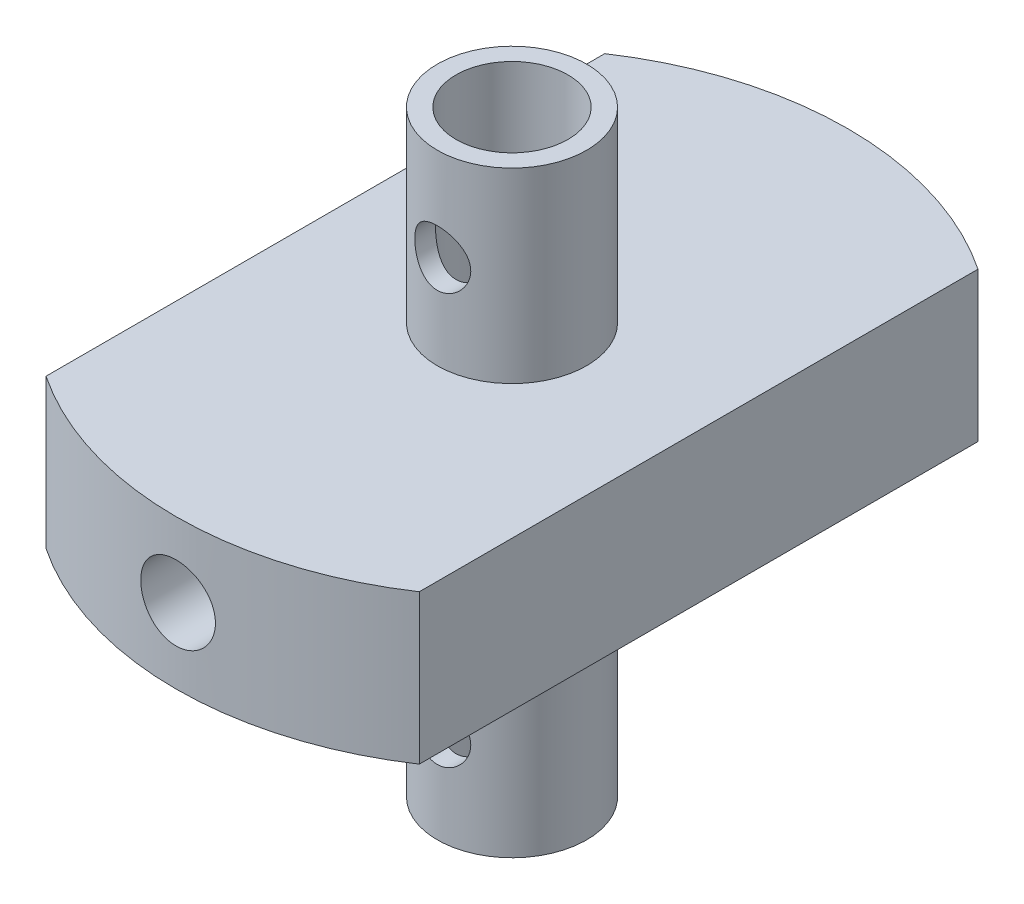
SolidWorks part; units mm, degrees
material "Delrin 2700 NC010, Low Viscosity Acetal Copolymer (SS)"
ref_plane "Front Plane" through (0, 0, 0) normal (0, 0, 1) x (1, 0, 0)
ref_plane "Top Plane" through (0, 0, 0) normal (0, 1, 0) x (1, 0, 0)
ref_plane "Right Plane" through (0, 0, 0) normal (1, 0, 0) x (0, 0, -1)
sketch "Sketch1" plane through (0, 0, 0) normal (0, 0, 1) x (1, 0, 0)
  line L0 (3, 0) -> (4, 0)
  line L1 (4, 0) -> (4, 14)
  line L2 (4, 14) -> (18, 14)
  line L3 (18, 14) -> (18, 22)
  line L4 (0, 0) -> (0, 39.5658) construction
  line L5 (0, 22) -> (18, 22)
  line L6 (3, 0) -> (3, 13)
  line L7 (3, 13) -> (0, 13)
  line L8 (0, 22) -> (0, 13)
  dimension "D1" = 22
  dimension "D2" = 6
  dimension "D3" = 8
  dimension "D4" = 8
  dimension "D5" = 36
  dimension "D6" = 13
revolve "Revolve1" add sketch "Sketch1" angle 360 about L4
sketch "Sketch2" plane through (0, 22, 0) normal (0, 1, 0) x (1, 0, 0)
  circle A0 centre (0, 0) radius 4
  circle A1 centre (0, 0) radius 3
  dimension "D1" = 8
  dimension "D2" = 6
extrude "Boss-Extrude1" add sketch "Sketch2" along normal blind 10
ref_plane "Plane1" through (0, 0, -4) normal (0, 0, -1) x (-1, 0, 0)
sketch "Sketch3" plane through (0, 0, -4) normal (0, 0, -1) x (-1, 0, 0)
  line L0 (-4, 0) -> (4, 0) construction
  line L1 (18, 22) -> (-18, 22) construction
  circle A0 centre (0, 5) radius 1.5
  circle A1 centre (0, 27) radius 1.5
  circle A2 centre (0, 18) radius 2
  dimension "D1" = 3
  dimension "D3" = 3
  dimension "D5" = 4
  dimension "D2" = 5
  dimension "D4" = 5
  dimension "D6" = 4
extrude "Cut-Extrude1" cut sketch "Sketch3" against normal through all both and the other way through all
sketch "Sketch4" plane through (0, 22, 0) normal (0, 1, 0) x (1, 0, 0)
  line L0 (0, 0) -> (0, 49.8965) construction
  line L1 (-23, 19) -> (-10, 19)
  line L2 (-10, 19) -> (-10, -19)
  line L3 (-10, -19) -> (-23, -19)
  line L4 (-23, -19) -> (-23, 19)
  line L5 (23, -19) -> (23, 19)
  line L6 (10, -19) -> (23, -19)
  line L7 (10, 19) -> (10, -19)
  line L8 (23, 19) -> (10, 19)
  dimension "D1" = 13
  dimension "D2" = 38
  dimension "D3" = 10
  dimension "D4" = 19
extrude "Cut-Extrude2" cut sketch "Sketch4" against normal blind 10
